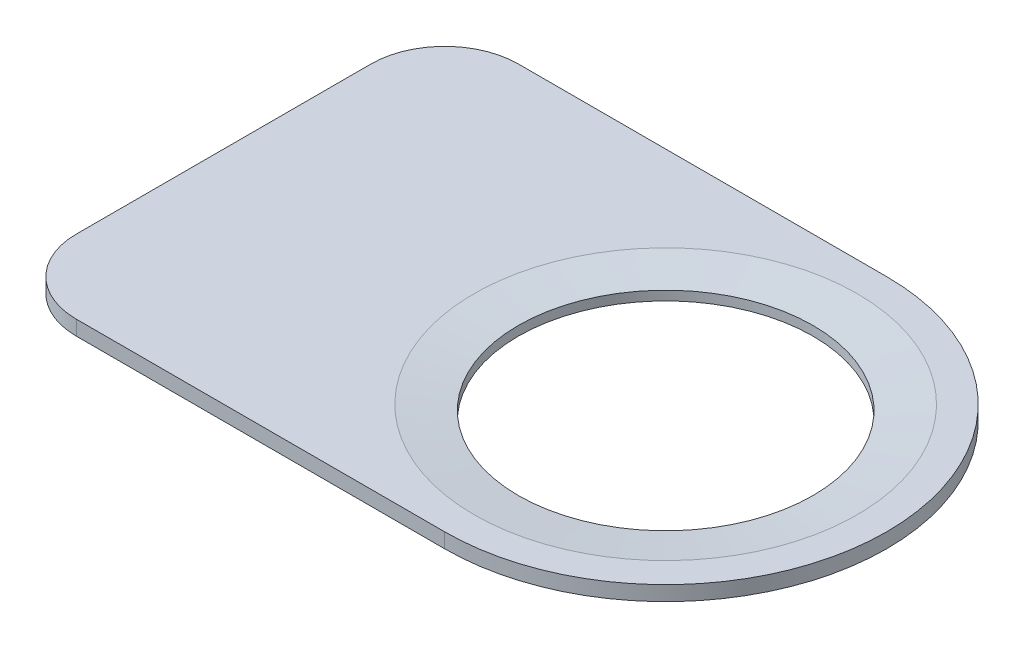
SolidWorks part; units mm, degrees
ref_plane "Front Plane" through (0, 0, 0) normal (0, 0, 1) x (1, 0, 0)
ref_plane "Top Plane" through (0, 0, 0) normal (0, 1, 0) x (1, 0, 0)
ref_plane "Right Plane" through (0, 0, 0) normal (1, 0, 0) x (0, 0, -1)
sketch "Sketch1" plane through (0, 0, 0) normal (0, 1, 0) x (1, 0, 0)
  line L1 (0, 15) -> (-25, 15)
  line L2 (0, 15) -> (0, -15)
  line L3 (0, -15) -> (-25, -15)
  line L4 (-30, 10) -> (-30, -10)
  circle A0 centre (0, 0) radius 10
  arc A1 (0, -15) -> (0, 15) centre (0, 0) ccw
  arc A2 (-25, -15) -> (-30, -10) centre (-25, -10) cw
  arc A3 (-25, 15) -> (-30, 10) centre (-25, 10) ccw
  point P11 (-30, 15)
  dimension "D1" = 20
  dimension "D2" = 5
  dimension "D4" = 5
  dimension "D3" = 30
extrude "Boss-Extrude1" add sketch "Sketch1" along normal blind 1 contours L1 A3 L4 A2 L3 L2 A0 | L2 A1 A0
chamfer "Chamfer1" distance 3 angle 7 1 edges at (0, 1, 10)
